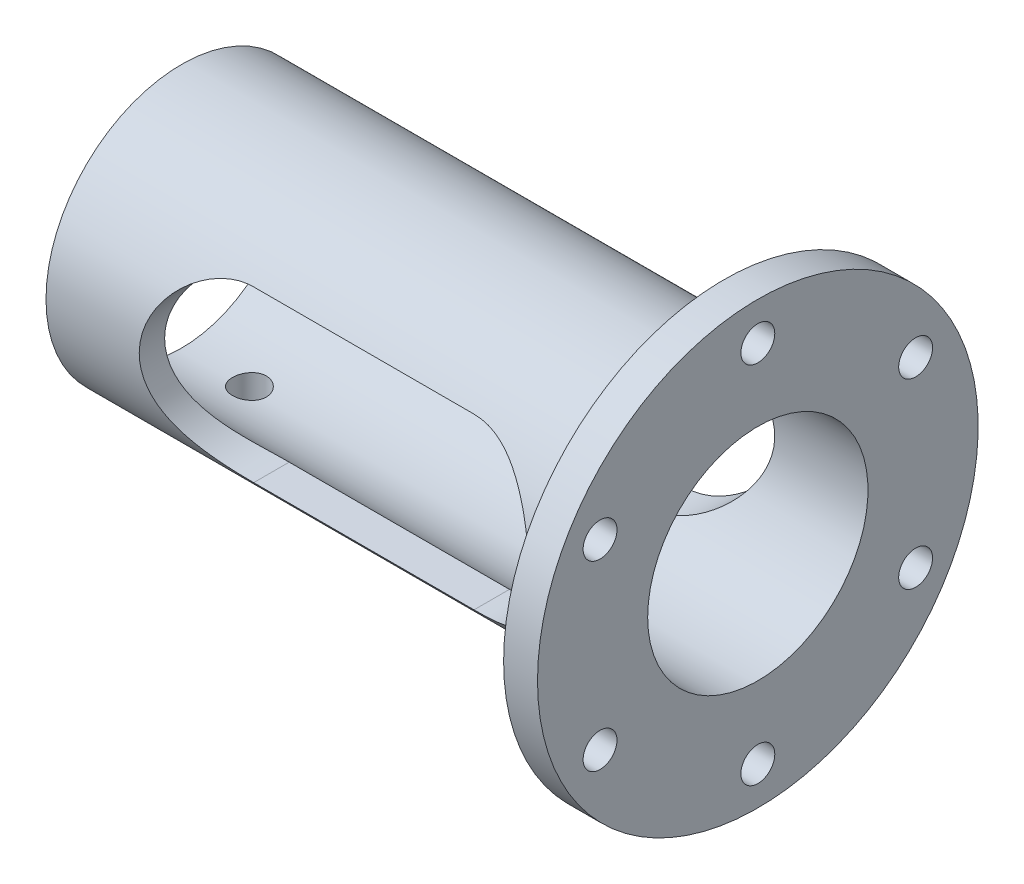
SolidWorks part; units mm, degrees
ref_plane "Front Plane" through (0, 0, 0) normal (0, 0, 1) x (1, 0, 0)
ref_plane "Top Plane" through (0, 0, 0) normal (0, 1, 0) x (1, 0, 0)
ref_plane "Right Plane" through (0, 0, 0) normal (1, 0, 0) x (0, 0, -1)
sketch "Sketch1" plane through (0, 0, 0) normal (0, 0, 1) x (1, 0, 0)
  line L0 (-47.0495, 0) -> (47.0495, 0) construction
  line L1 (-34, 13) -> (-34, 16)
  line L2 (-34, 16) -> (30, 16)
  line L3 (30, 16) -> (30, 26)
  line L4 (30, 26) -> (34, 26)
  line L5 (34, 26) -> (34, 13)
  line L6 (34, 13) -> (-34, 13)
  point P0 (-34, 14.5)
  point P4 (0, 0)
  point P14 (0, 13)
  dimension "D1" = 13
  dimension "D2" = 16
  dimension "D3" = 26
  dimension "D4" = 4
  dimension "D5" = 64
revolve "Revolve1" add sketch "Sketch1" angle 360 about L0
sketch "Sketch2" plane through (34, 0, 0) normal (1, 0, 0) x (0, 0, -1)
  circle A0 centre (0, 0) radius 21.5 construction
  circle A4 centre (0, -21.5) radius 2
  circle A5 centre (0, 0) radius 26 construction
  circle A6 centre (-18.6195, -10.75) radius 2
  circle A7 centre (-18.6195, 10.75) radius 2
  circle A8 centre (0, 21.5) radius 2
  circle A9 centre (18.6195, 10.75) radius 2
  circle A10 centre (18.6195, -10.75) radius 2
  dimension "D1" = 6
  dimension "D2" = 4
  dimension "D5" = 43
extrude "Cut-Extrude1" cut sketch "Sketch2" against normal through all
sketch "Sketch4" plane through (0, 0, 0) normal (0, 0, 1) x (1, 0, 0)
  line L0 (-13, 0) -> (13, 0) construction
  line L2 (-13, 10) -> (13, 10)
  line L3 (-13, -10) -> (13, -10)
  arc A0 (-13, 10) -> (-13, -10) centre (-13, 0) ccw
  arc A1 (13, -10) -> (13, 10) centre (13, 0) ccw
  point P5 (0, 0)
  dimension "D1" = 20
  dimension "D2" = 26
extrude "Cut-Extrude2" cut sketch "Sketch4" against normal through all both and the other way through all
sketch "Sketch5" plane through (0, 0, 0) normal (0, 1, 0) x (1, 0, 0)
  circle A0 centre (-26, 0) radius 2
  circle A1 centre (13, 0) radius 2
  dimension "D1" = 4
  dimension "D2" = 13
  dimension "D3" = 26
extrude "Cut-Extrude3" cut sketch "Sketch5" along normal blind 1 and the other way through all
